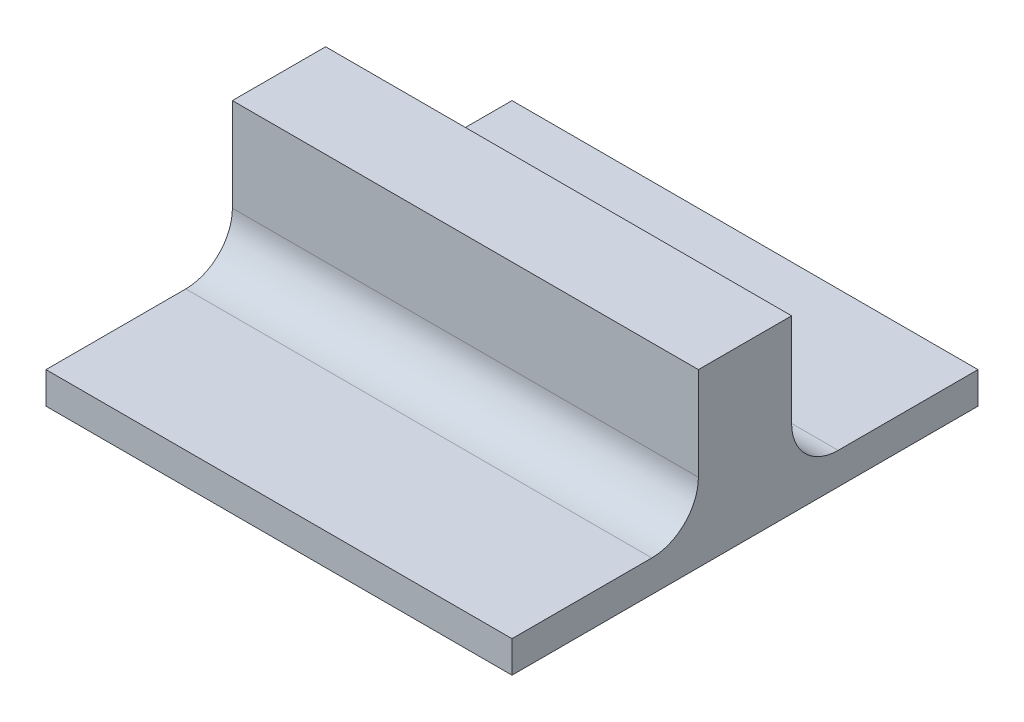
SolidWorks part; units mm, degrees
ref_plane "Front Plane" through (0, 0, 0) normal (0, 0, 1) x (1, 0, 0)
ref_plane "Top Plane" through (0, 0, 0) normal (0, 1, 0) x (1, 0, 0)
ref_plane "Right Plane" through (0, 0, 0) normal (1, 0, 0) x (0, 0, -1)
sketch "Sketch1" plane through (0, 0, 0) normal (0, 1, 0) x (1, 0, 0)
  line L0 (-13.0678, 20) -> (-14.2225, 22)
  line L1 (-25, -25) -> (25, -25)
  line L2 (-25, -25) -> (-25, 25)
  line L3 (-25, 25) -> (25, 25)
  line L4 (25, -25) -> (25, 25)
  line L5 (-25, -25) -> (25, 25) construction
  line L6 (-25, 25) -> (25, -25) construction
  line L7 (-19.2187, 20) -> (-20.3734, 22)
  line L8 (-20.3734, 22) -> (-22.6828, 22)
  line L9 (-22.6828, 22) -> (-23.8375, 20)
  line L10 (-23.8375, 20) -> (-22.6828, 18)
  line L11 (-22.6828, 18) -> (-20.3734, 18)
  line L12 (-20.3734, 18) -> (-19.2187, 20)
  line L13 (-14.2225, 22) -> (-16.5319, 22)
  line L14 (-16.5319, 22) -> (-17.6866, 20)
  line L15 (-17.6866, 20) -> (-16.5319, 18)
  line L16 (-16.5319, 18) -> (-14.2225, 18)
  line L17 (-14.2225, 18) -> (-13.0678, 20)
  line L18 (-6.9169, 20) -> (-8.0716, 22)
  line L19 (-8.0716, 22) -> (-10.381, 22)
  line L20 (-10.381, 22) -> (-11.5357, 20)
  line L21 (-11.5357, 20) -> (-10.381, 18)
  line L22 (-10.381, 18) -> (-8.0716, 18)
  line L23 (-8.0716, 18) -> (-6.9169, 20)
  line L24 (-0.766, 20) -> (-1.9207, 22)
  line L25 (-1.9207, 22) -> (-4.2301, 22)
  line L26 (-4.2301, 22) -> (-5.3848, 20)
  line L27 (-5.3848, 20) -> (-4.2301, 18)
  line L28 (-4.2301, 18) -> (-1.9207, 18)
  line L29 (-1.9207, 18) -> (-0.766, 20)
  line L30 (5.3848, 20) -> (4.2301, 22)
  line L31 (4.2301, 22) -> (1.9207, 22)
  line L32 (1.9207, 22) -> (0.766, 20)
  line L33 (0.766, 20) -> (1.9207, 18)
  line L34 (1.9207, 18) -> (4.2301, 18)
  line L35 (4.2301, 18) -> (5.3848, 20)
  line L36 (11.5357, 20) -> (10.381, 22)
  line L37 (10.381, 22) -> (8.0716, 22)
  line L38 (8.0716, 22) -> (6.9169, 20)
  line L39 (6.9169, 20) -> (8.0716, 18)
  line L40 (8.0716, 18) -> (10.381, 18)
  line L41 (10.381, 18) -> (11.5357, 20)
  line L42 (17.6866, 20) -> (16.5319, 22)
  line L43 (16.5319, 22) -> (14.2225, 22)
  line L44 (14.2225, 22) -> (13.0678, 20)
  line L45 (13.0678, 20) -> (14.2225, 18)
  line L46 (14.2225, 18) -> (16.5319, 18)
  line L47 (16.5319, 18) -> (17.6866, 20)
  line L48 (23.8375, 20) -> (22.6828, 22)
  line L49 (22.6828, 22) -> (20.3734, 22)
  line L50 (20.3734, 22) -> (19.2187, 20)
  line L51 (19.2187, 20) -> (20.3734, 18)
  line L52 (20.3734, 18) -> (22.6828, 18)
  line L53 (22.6828, 18) -> (23.8375, 20)
  line L54 (-13.0678, 12) -> (-14.2225, 14)
  line L55 (-14.2225, 14) -> (-16.5319, 14)
  line L56 (-16.5319, 14) -> (-17.6866, 12)
  line L57 (-17.6866, 12) -> (-16.5319, 10)
  line L58 (-16.5319, 10) -> (-14.2225, 10)
  line L59 (-14.2225, 10) -> (-13.0678, 12)
  line L60 (-6.9169, 12) -> (-8.0716, 14)
  line L61 (-8.0716, 14) -> (-10.381, 14)
  line L62 (-10.381, 14) -> (-11.5357, 12)
  line L63 (-11.5357, 12) -> (-10.381, 10)
  line L64 (-10.381, 10) -> (-8.0716, 10)
  line L65 (-8.0716, 10) -> (-6.9169, 12)
  line L66 (-0.766, 12) -> (-1.9207, 14)
  line L67 (-1.9207, 14) -> (-4.2301, 14)
  line L68 (-4.2301, 14) -> (-5.3848, 12)
  line L69 (-5.3848, 12) -> (-4.2301, 10)
  line L70 (-4.2301, 10) -> (-1.9207, 10)
  line L71 (-1.9207, 10) -> (-0.766, 12)
  line L72 (5.3848, 12) -> (4.2301, 14)
  line L73 (4.2301, 14) -> (1.9207, 14)
  line L74 (1.9207, 14) -> (0.766, 12)
  line L75 (0.766, 12) -> (1.9207, 10)
  line L76 (1.9207, 10) -> (4.2301, 10)
  line L77 (4.2301, 10) -> (5.3848, 12)
  line L78 (11.5357, 12) -> (10.381, 14)
  line L79 (10.381, 14) -> (8.0716, 14)
  line L80 (8.0716, 14) -> (6.9169, 12)
  line L81 (6.9169, 12) -> (8.0716, 10)
  line L82 (8.0716, 10) -> (10.381, 10)
  line L83 (10.381, 10) -> (11.5357, 12)
  line L84 (17.6866, 12) -> (16.5319, 14)
  line L85 (16.5319, 14) -> (14.2225, 14)
  line L86 (14.2225, 14) -> (13.0678, 12)
  line L87 (13.0678, 12) -> (14.2225, 10)
  line L88 (14.2225, 10) -> (16.5319, 10)
  line L89 (16.5319, 10) -> (17.6866, 12)
  line L90 (23.8375, 12) -> (22.6828, 14)
  line L91 (22.6828, 14) -> (20.3734, 14)
  line L92 (20.3734, 14) -> (19.2187, 12)
  line L93 (19.2187, 12) -> (20.3734, 10)
  line L94 (20.3734, 10) -> (22.6828, 10)
  line L95 (22.6828, 10) -> (23.8375, 12)
  line L96 (-13.0678, 4) -> (-14.2225, 6)
  line L97 (-14.2225, 6) -> (-16.5319, 6)
  line L98 (-16.5319, 6) -> (-17.6866, 4)
  line L99 (-17.6866, 4) -> (-16.5319, 2)
  line L100 (-16.5319, 2) -> (-14.2225, 2)
  line L101 (-14.2225, 2) -> (-13.0678, 4)
  line L102 (-6.9169, 4) -> (-8.0716, 6)
  line L103 (-8.0716, 6) -> (-10.381, 6)
  line L104 (-10.381, 6) -> (-11.5357, 4)
  line L105 (-11.5357, 4) -> (-10.381, 2)
  line L106 (-10.381, 2) -> (-8.0716, 2)
  line L107 (-8.0716, 2) -> (-6.9169, 4)
  line L108 (-0.766, 4) -> (-1.9207, 6)
  line L109 (-1.9207, 6) -> (-4.2301, 6)
  line L110 (-4.2301, 6) -> (-5.3848, 4)
  line L111 (-5.3848, 4) -> (-4.2301, 2)
  line L112 (-4.2301, 2) -> (-1.9207, 2)
  line L113 (-1.9207, 2) -> (-0.766, 4)
  line L114 (5.3848, 4) -> (4.2301, 6)
  line L115 (4.2301, 6) -> (1.9207, 6)
  line L116 (1.9207, 6) -> (0.766, 4)
  line L117 (0.766, 4) -> (1.9207, 2)
  line L118 (1.9207, 2) -> (4.2301, 2)
  line L119 (4.2301, 2) -> (5.3848, 4)
  line L120 (11.5357, 4) -> (10.381, 6)
  line L121 (10.381, 6) -> (8.0716, 6)
  line L122 (8.0716, 6) -> (6.9169, 4)
  line L123 (6.9169, 4) -> (8.0716, 2)
  line L124 (8.0716, 2) -> (10.381, 2)
  line L125 (10.381, 2) -> (11.5357, 4)
  line L126 (17.6866, 4) -> (16.5319, 6)
  line L127 (16.5319, 6) -> (14.2225, 6)
  line L128 (14.2225, 6) -> (13.0678, 4)
  line L129 (13.0678, 4) -> (14.2225, 2)
  line L130 (14.2225, 2) -> (16.5319, 2)
  line L131 (16.5319, 2) -> (17.6866, 4)
  line L132 (23.8375, 4) -> (22.6828, 6)
  line L133 (22.6828, 6) -> (20.3734, 6)
  line L134 (20.3734, 6) -> (19.2187, 4)
  line L135 (19.2187, 4) -> (20.3734, 2)
  line L136 (20.3734, 2) -> (22.6828, 2)
  line L137 (22.6828, 2) -> (23.8375, 4)
  line L138 (-13.0678, -4) -> (-14.2225, -2)
  line L139 (-14.2225, -2) -> (-16.5319, -2)
  line L140 (-16.5319, -2) -> (-17.6866, -4)
  line L141 (-17.6866, -4) -> (-16.5319, -6)
  line L142 (-16.5319, -6) -> (-14.2225, -6)
  line L143 (-14.2225, -6) -> (-13.0678, -4)
  line L144 (-6.9169, -4) -> (-8.0716, -2)
  line L145 (-8.0716, -2) -> (-10.381, -2)
  line L146 (-10.381, -2) -> (-11.5357, -4)
  line L147 (-11.5357, -4) -> (-10.381, -6)
  line L148 (-10.381, -6) -> (-8.0716, -6)
  line L149 (-8.0716, -6) -> (-6.9169, -4)
  line L150 (-0.766, -4) -> (-1.9207, -2)
  line L151 (-1.9207, -2) -> (-4.2301, -2)
  line L152 (-4.2301, -2) -> (-5.3848, -4)
  line L153 (-5.3848, -4) -> (-4.2301, -6)
  line L154 (-4.2301, -6) -> (-1.9207, -6)
  line L155 (-1.9207, -6) -> (-0.766, -4)
  line L156 (5.3848, -4) -> (4.2301, -2)
  line L157 (4.2301, -2) -> (1.9207, -2)
  line L158 (1.9207, -2) -> (0.766, -4)
  line L159 (0.766, -4) -> (1.9207, -6)
  line L160 (1.9207, -6) -> (4.2301, -6)
  line L161 (4.2301, -6) -> (5.3848, -4)
  line L162 (11.5357, -4) -> (10.381, -2)
  line L163 (10.381, -2) -> (8.0716, -2)
  line L164 (8.0716, -2) -> (6.9169, -4)
  line L165 (6.9169, -4) -> (8.0716, -6)
  line L166 (8.0716, -6) -> (10.381, -6)
  line L167 (10.381, -6) -> (11.5357, -4)
  line L168 (17.6866, -4) -> (16.5319, -2)
  line L169 (16.5319, -2) -> (14.2225, -2)
  line L170 (14.2225, -2) -> (13.0678, -4)
  line L171 (13.0678, -4) -> (14.2225, -6)
  line L172 (14.2225, -6) -> (16.5319, -6)
  line L173 (16.5319, -6) -> (17.6866, -4)
  line L174 (23.8375, -4) -> (22.6828, -2)
  line L175 (22.6828, -2) -> (20.3734, -2)
  line L176 (20.3734, -2) -> (19.2187, -4)
  line L177 (19.2187, -4) -> (20.3734, -6)
  line L178 (20.3734, -6) -> (22.6828, -6)
  line L179 (22.6828, -6) -> (23.8375, -4)
  line L180 (-13.0678, -12) -> (-14.2225, -10)
  line L181 (-14.2225, -10) -> (-16.5319, -10)
  line L182 (-16.5319, -10) -> (-17.6866, -12)
  line L183 (-17.6866, -12) -> (-16.5319, -14)
  line L184 (-16.5319, -14) -> (-14.2225, -14)
  line L185 (-14.2225, -14) -> (-13.0678, -12)
  line L186 (-6.9169, -12) -> (-8.0716, -10)
  line L187 (-8.0716, -10) -> (-10.381, -10)
  line L188 (-10.381, -10) -> (-11.5357, -12)
  line L189 (-11.5357, -12) -> (-10.381, -14)
  line L190 (-10.381, -14) -> (-8.0716, -14)
  line L191 (-8.0716, -14) -> (-6.9169, -12)
  line L192 (-0.766, -12) -> (-1.9207, -10)
  line L193 (-1.9207, -10) -> (-4.2301, -10)
  line L194 (-4.2301, -10) -> (-5.3848, -12)
  line L195 (-5.3848, -12) -> (-4.2301, -14)
  line L196 (-4.2301, -14) -> (-1.9207, -14)
  line L197 (-1.9207, -14) -> (-0.766, -12)
  line L198 (5.3848, -12) -> (4.2301, -10)
  line L199 (4.2301, -10) -> (1.9207, -10)
  line L200 (1.9207, -10) -> (0.766, -12)
  line L201 (0.766, -12) -> (1.9207, -14)
  line L202 (1.9207, -14) -> (4.2301, -14)
  line L203 (4.2301, -14) -> (5.3848, -12)
  line L204 (11.5357, -12) -> (10.381, -10)
  line L205 (10.381, -10) -> (8.0716, -10)
  line L206 (8.0716, -10) -> (6.9169, -12)
  line L207 (6.9169, -12) -> (8.0716, -14)
  line L208 (8.0716, -14) -> (10.381, -14)
  line L209 (10.381, -14) -> (11.5357, -12)
  line L210 (17.6866, -12) -> (16.5319, -10)
  line L211 (16.5319, -10) -> (14.2225, -10)
  line L212 (14.2225, -10) -> (13.0678, -12)
  line L213 (13.0678, -12) -> (14.2225, -14)
  line L214 (14.2225, -14) -> (16.5319, -14)
  line L215 (16.5319, -14) -> (17.6866, -12)
  line L216 (23.8375, -12) -> (22.6828, -10)
  line L217 (22.6828, -10) -> (20.3734, -10)
  line L218 (20.3734, -10) -> (19.2187, -12)
  line L219 (19.2187, -12) -> (20.3734, -14)
  line L220 (20.3734, -14) -> (22.6828, -14)
  line L221 (22.6828, -14) -> (23.8375, -12)
  line L222 (-13.0678, -20) -> (-14.2225, -18)
  line L223 (-14.2225, -18) -> (-16.5319, -18)
  line L224 (-16.5319, -18) -> (-17.6866, -20)
  line L225 (-17.6866, -20) -> (-16.5319, -22)
  line L226 (-16.5319, -22) -> (-14.2225, -22)
  line L227 (-14.2225, -22) -> (-13.0678, -20)
  line L228 (-6.9169, -20) -> (-8.0716, -18)
  line L229 (-8.0716, -18) -> (-10.381, -18)
  line L230 (-10.381, -18) -> (-11.5357, -20)
  line L231 (-11.5357, -20) -> (-10.381, -22)
  line L232 (-10.381, -22) -> (-8.0716, -22)
  line L233 (-8.0716, -22) -> (-6.9169, -20)
  line L234 (-0.766, -20) -> (-1.9207, -18)
  line L235 (-1.9207, -18) -> (-4.2301, -18)
  line L236 (-4.2301, -18) -> (-5.3848, -20)
  line L237 (-5.3848, -20) -> (-4.2301, -22)
  line L238 (-4.2301, -22) -> (-1.9207, -22)
  line L239 (-1.9207, -22) -> (-0.766, -20)
  line L240 (5.3848, -20) -> (4.2301, -18)
  line L241 (4.2301, -18) -> (1.9207, -18)
  line L242 (1.9207, -18) -> (0.766, -20)
  line L243 (0.766, -20) -> (1.9207, -22)
  line L244 (1.9207, -22) -> (4.2301, -22)
  line L245 (4.2301, -22) -> (5.3848, -20)
  line L246 (11.5357, -20) -> (10.381, -18)
  line L247 (10.381, -18) -> (8.0716, -18)
  line L248 (8.0716, -18) -> (6.9169, -20)
  line L249 (6.9169, -20) -> (8.0716, -22)
  line L250 (8.0716, -22) -> (10.381, -22)
  line L251 (10.381, -22) -> (11.5357, -20)
  line L252 (17.6866, -20) -> (16.5319, -18)
  line L253 (16.5319, -18) -> (14.2225, -18)
  line L254 (14.2225, -18) -> (13.0678, -20)
  line L255 (13.0678, -20) -> (14.2225, -22)
  line L256 (14.2225, -22) -> (16.5319, -22)
  line L257 (16.5319, -22) -> (17.6866, -20)
  line L258 (23.8375, -20) -> (22.6828, -18)
  line L259 (22.6828, -18) -> (20.3734, -18)
  line L260 (20.3734, -18) -> (19.2187, -20)
  line L261 (19.2187, -20) -> (20.3734, -22)
  line L262 (20.3734, -22) -> (22.6828, -22)
  line L263 (22.6828, -22) -> (23.8375, -20)
  line L264 (-19.2187, 12) -> (-20.3734, 14)
  line L265 (-20.3734, 14) -> (-22.6828, 14)
  line L266 (-22.6828, 14) -> (-23.8375, 12)
  line L267 (-23.8375, 12) -> (-22.6828, 10)
  line L268 (-22.6828, 10) -> (-20.3734, 10)
  line L269 (-20.3734, 10) -> (-19.2187, 12)
  line L270 (-19.2187, 4) -> (-20.3734, 6)
  line L271 (-20.3734, 6) -> (-22.6828, 6)
  line L272 (-22.6828, 6) -> (-23.8375, 4)
  line L273 (-23.8375, 4) -> (-22.6828, 2)
  line L274 (-22.6828, 2) -> (-20.3734, 2)
  line L275 (-20.3734, 2) -> (-19.2187, 4)
  line L276 (-19.2187, -4) -> (-20.3734, -2)
  line L277 (-20.3734, -2) -> (-22.6828, -2)
  line L278 (-22.6828, -2) -> (-23.8375, -4)
  line L279 (-23.8375, -4) -> (-22.6828, -6)
  line L280 (-22.6828, -6) -> (-20.3734, -6)
  line L281 (-20.3734, -6) -> (-19.2187, -4)
  line L282 (-19.2187, -12) -> (-20.3734, -10)
  line L283 (-20.3734, -10) -> (-22.6828, -10)
  line L284 (-22.6828, -10) -> (-23.8375, -12)
  line L285 (-23.8375, -12) -> (-22.6828, -14)
  line L286 (-22.6828, -14) -> (-20.3734, -14)
  line L287 (-20.3734, -14) -> (-19.2187, -12)
  line L288 (-19.2187, -20) -> (-20.3734, -18)
  line L289 (-20.3734, -18) -> (-22.6828, -18)
  line L290 (-22.6828, -18) -> (-23.8375, -20)
  line L291 (-23.8375, -20) -> (-22.6828, -22)
  line L292 (-22.6828, -22) -> (-20.3734, -22)
  line L293 (-20.3734, -22) -> (-19.2187, -20)
  line L294 (23.8375, 20) -> (25, 20) construction
  line L295 (-23.8375, 20) -> (-25, 20) construction
  circle A1 centre (-21.5281, 20) radius 2 construction
  circle A2 centre (-15.3772, 20) radius 2 construction
  circle A3 centre (-9.2263, 20) radius 2 construction
  circle A4 centre (-3.0754, 20) radius 2 construction
  circle A5 centre (3.0754, 20) radius 2 construction
  circle A6 centre (9.2263, 20) radius 2 construction
  circle A7 centre (15.3772, 20) radius 2 construction
  circle A8 centre (21.5281, 20) radius 2 construction
  circle A9 centre (-15.3772, 12) radius 2 construction
  circle A10 centre (-9.2263, 12) radius 2 construction
  circle A11 centre (-3.0754, 12) radius 2 construction
  circle A12 centre (3.0754, 12) radius 2 construction
  circle A13 centre (9.2263, 12) radius 2 construction
  circle A14 centre (15.3772, 12) radius 2 construction
  circle A15 centre (21.5281, 12) radius 2 construction
  circle A16 centre (-15.3772, 4) radius 2 construction
  circle A17 centre (-9.2263, 4) radius 2 construction
  circle A18 centre (-3.0754, 4) radius 2 construction
  circle A19 centre (3.0754, 4) radius 2 construction
  circle A20 centre (9.2263, 4) radius 2 construction
  circle A21 centre (15.3772, 4) radius 2 construction
  circle A22 centre (21.5281, 4) radius 2 construction
  circle A23 centre (-15.3772, -4) radius 2 construction
  circle A24 centre (-9.2263, -4) radius 2 construction
  circle A25 centre (-3.0754, -4) radius 2 construction
  circle A26 centre (3.0754, -4) radius 2 construction
  circle A27 centre (9.2263, -4) radius 2 construction
  circle A28 centre (15.3772, -4) radius 2 construction
  circle A29 centre (21.5281, -4) radius 2 construction
  circle A30 centre (-15.3772, -12) radius 2 construction
  circle A31 centre (-9.2263, -12) radius 2 construction
  circle A32 centre (-3.0754, -12) radius 2 construction
  circle A33 centre (3.0754, -12) radius 2 construction
  circle A34 centre (9.2263, -12) radius 2 construction
  circle A35 centre (15.3772, -12) radius 2 construction
  circle A36 centre (21.5281, -12) radius 2 construction
  circle A37 centre (-15.3772, -20) radius 2 construction
  circle A38 centre (-9.2263, -20) radius 2 construction
  circle A39 centre (-3.0754, -20) radius 2 construction
  circle A40 centre (3.0754, -20) radius 2 construction
  circle A41 centre (9.2263, -20) radius 2 construction
  circle A42 centre (15.3772, -20) radius 2 construction
  circle A43 centre (21.5281, -20) radius 2 construction
  circle A44 centre (-21.5281, 12) radius 2 construction
  circle A45 centre (-21.5281, 4) radius 2 construction
  circle A46 centre (-21.5281, -4) radius 2 construction
  circle A47 centre (-21.5281, -12) radius 2 construction
  circle A48 centre (-21.5281, -20) radius 2 construction
  point P0 (0, 0)
  point P7 (0, 0)
  point P393 (0, 0)
  dimension "D4" = 5
  dimension "D5" = 8
  dimension "D1" = 50
  dimension "D2" = 50
  dimension "D3" = 4
  dimension "D7" = 5
  dimension "D6" = 6
extrude "Boss-Extrude1" add sketch "Sketch1" along normal blind 1.4
sketch "Sketch2" plane through (0, 1.4, 0) normal (0, 1, 0) x (1, 0, 0)
  line L1 (-25, -25) -> (25, -25)
  line L2 (-25, -25) -> (-25, 25)
  line L3 (-25, 25) -> (25, 25)
  line L4 (25, -25) -> (25, 25)
extrude "Boss-Extrude2" add sketch "Sketch2" along normal blind 2
sketch "Sketch3" plane through (0, 3.4, 0) normal (0, 1, 0) x (1, 0, 0)
  line L0 (25, -25) -> (25, 25) construction
  line L1 (-25, -5) -> (25, -5)
  line L2 (-25, -5) -> (-25, 5)
  line L3 (-25, 5) -> (25, 5)
  line L4 (25, -5) -> (25, 5)
  line L5 (-25, -5) -> (25, 5) construction
  line L6 (-25, 5) -> (25, -5) construction
  point P0 (0, 0)
  dimension "D1" = 10
extrude "Boss-Extrude3" add sketch "Sketch3" along normal blind 15
fillet "Fillet1" radius 5 2 edges at (0, 3.4, -5) (0, 3.4, 5)
